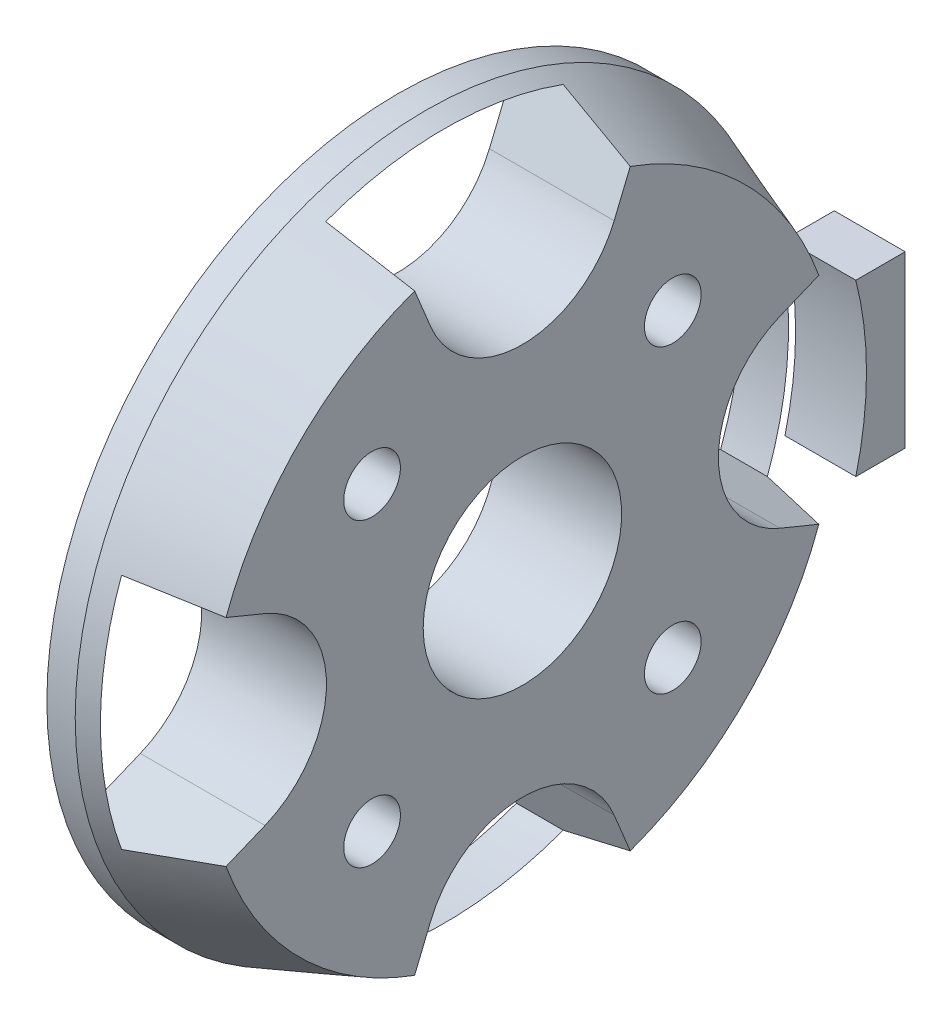
SolidWorks part; units mm, degrees
ref_plane "Front Plane" through (0, 0, 0) normal (0, 0, 1) x (1, 0, 0)
ref_plane "Top Plane" through (0, 0, 0) normal (0, 1, 0) x (1, 0, 0)
ref_plane "Right Plane" through (0, 0, 0) normal (1, 0, 0) x (0, 0, -1)
sketch "Sketch2" plane through (0, 0, 0) normal (0, 0, 1) x (1, 0, 0)
  line L0 (0, 0) -> (51.0154, 0) construction
  line L1 (0, 24.75) -> (2, 24.75)
  line L2 (2, 24.75) -> (8.8, 22.25)
  line L3 (8.8, 22.25) -> (8.8, 7)
  line L4 (8.8, 7) -> (0, 7)
  line L5 (0, 7) -> (0, 24.75)
  dimension "D1" = 8.8
  dimension "D2" = 2
  dimension "D3" = 2.5
  dimension "D4" = 14
  dimension "D5" = 49.5
revolve "Revolve1" add sketch "Sketch2" angle 360 about L0
sketch "Sketch3" plane through (8.8, 0, 0) normal (1, 0, 0) x (0, 0, -1)
  line L0 (0, 0) -> (10.6066, 10.6066) construction
  line L1 (0, 0) -> (5.0555, 0) construction
  circle A0 centre (10.6066, 10.6066) radius 2
  circle A1 centre (10.6066, -10.6066) radius 2
  circle A2 centre (-10.6066, -10.6066) radius 2
  circle A3 centre (-10.6066, 10.6066) radius 2
  point P14 (0, 0)
  dimension "D2" = 4
  dimension "D1" = 45
  dimension "D3" = 15
  dimension "D4" = 4
extrude "Cut-Extrude1" cut sketch "Sketch3" against normal blind 5
sketch "Sketch4" plane through (8.8, 0, 0) normal (1, 0, 0) x (0, 0, -1)
  line L0 (0, 0) -> (15, 0) construction
  line L1 (15, 6) -> (27, 6)
  line L2 (15, 6) -> (15, -6)
  line L3 (15, -6) -> (27, -6)
  line L4 (27, 6) -> (27, -6)
  dimension "D1" = 12
  dimension "D2" = 12
  dimension "D3" = 15
extrude "Boss-Extrude1" add sketch "Sketch4" against normal blind 5
sketch "Sketch6" plane through (8.8, 0, 0) normal (1, 0, 0) x (0, 0, -1)
  line L0 (8.8598, 93.3826) -> (181.5264, 93.3826) construction
  line L1 (-6.4723, 18.1576) -> (-7.606, 20.9096)
  line L2 (6.4723, 18.1576) -> (7.606, 20.9096)
  line L3 (0, 0) -> (0, 20.8239) construction
  line L4 (-7.606, 20.9096) -> (-8.3768, 22.7807)
  line L5 (7.606, 20.9096) -> (8.3768, 22.7807)
  arc A0 (-6.4723, 18.1576) -> (6.4723, 18.1576) centre (0, 20.8239) ccw
  arc A1 (-7.606, 20.9096) -> (7.606, 20.9096) centre (0, 0) cw construction
  arc A2 (21.4257, 6) -> (21.4257, -6) centre (0, 0) ccw construction
  arc A3 (8.3768, 22.7807) -> (-8.3768, 22.7807) centre (0, 0) ccw
  point P5 (0, 0)
  dimension "D1" = 7
  dimension "D2" = 5
extrude "Cut-Extrude2" cut sketch "Sketch6" against normal through all
pattern_circular "CirPattern1" count 4 over 360 about axis through (0, 0, 0) along (1, 0, 0) of "Cut-Extrude2"
